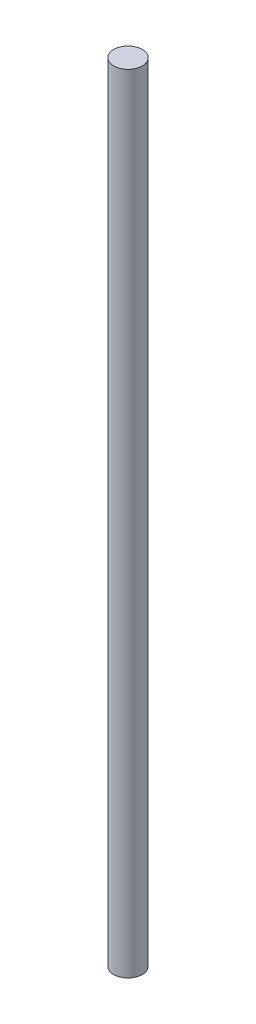
SolidWorks part; units mm, degrees
material "AISI 1020"
ref_plane "Front Plane" through (0, 0, 0) normal (0, 0, 1) x (1, 0, 0)
ref_plane "Top Plane" through (0, 0, 0) normal (0, 1, 0) x (1, 0, 0)
ref_plane "Right Plane" through (0, 0, 0) normal (1, 0, 0) x (0, 0, -1)
sketch "Sketch1" plane through (0, 0, 0) normal (0, 1, 0) x (1, 0, 0)
  circle A0 centre (-5.3268, 0) radius 3
  dimension "D1" = 6
extrude "Boss-Extrude1" add sketch "Sketch1" along normal blind 165
